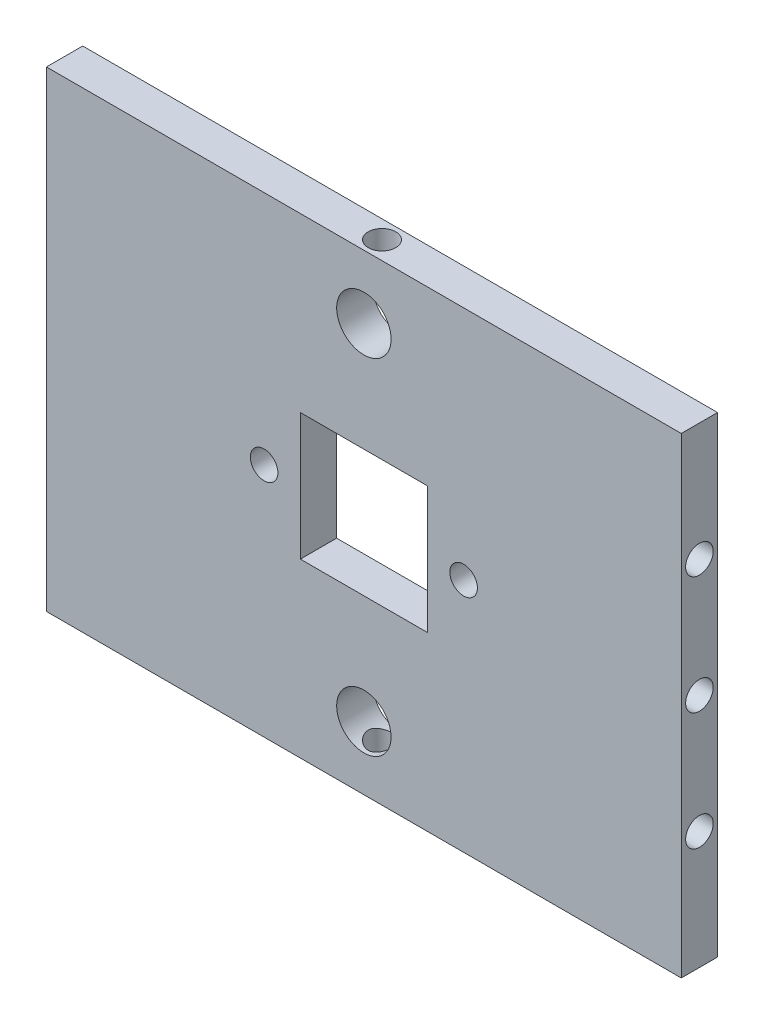
SolidWorks part; units mm, degrees
material "Plain Carbon Steel"
ref_plane "Front Plane" through (0, 0, 0) normal (0, 0, 1) x (1, 0, 0)
ref_plane "Top Plane" through (0, 0, 0) normal (0, 1, 0) x (1, 0, 0)
ref_plane "Right Plane" through (0, 0, 0) normal (1, 0, 0) x (0, 0, -1)
sketch "Sketch1" plane through (0, 0, 0) normal (0, 0, 1) x (1, 0, 0)
  line L1 (55.5625, -41.275) -> (-55.5625, -41.275)
  line L2 (55.5625, -41.275) -> (55.5625, 41.275)
  line L3 (55.5625, 41.275) -> (-55.5625, 41.275)
  line L4 (-55.5625, -41.275) -> (-55.5625, 41.275)
  line L5 (55.5625, -41.275) -> (-55.5625, 41.275) construction
  line L6 (55.5625, 41.275) -> (-55.5625, -41.275) construction
  circle A0 centre (0, 30.1625) radius 4.7625
  circle A1 centre (0, -30.1625) radius 4.7625
  point P0 (0, 0)
  dimension "D3" = 9.525
  dimension "D4" = 9.525
  dimension "D1" = 82.55
  dimension "D2" = 111.125
extrude "Boss-Extrude1" add sketch "Sketch1" along normal blind 6.35
sketch "Sketch2" plane through (55.5625, 0, 0) normal (1, 0, 0) x (0, 0, -1)
  line L0 (-3.175, 41.275) -> (-3.175, 0) construction
  line L1 (-6.35, 41.275) -> (0, 41.275) construction
  line L2 (-3.175, 0) -> (-3.175, -41.275) construction
  line L3 (-6.35, -41.275) -> (0, -41.275) construction
  circle A0 centre (-3.175, 20.6375) radius 2.413
  circle A1 centre (-3.175, 0) radius 2.413
  circle A2 centre (-3.175, -20.6375) radius 2.413
  dimension "D1" = 4.826
  dimension "D2" = 4.826
  dimension "D3" = 4.826
extrude "Cut-Extrude1" cut sketch "Sketch2" against normal blind 12.7
mirror "Mirror1" about plane through (0, 0, 0) normal (1, 0, 0) of "Cut-Extrude1"
sketch "Sketch3" plane through (0, 41.275, 0) normal (0, 1, 0) x (1, 0, 0)
  line L0 (-55.5625, -3.175) -> (55.5625, -3.175) construction
  line L1 (-55.5625, -6.35) -> (-55.5625, 0) construction
  line L2 (55.5625, -6.35) -> (55.5625, 0) construction
  circle A0 centre (0, -3.175) radius 2.413
  dimension "D1" = 4.826
extrude "Cut-Extrude2" cut sketch "Sketch3" against normal blind 12.7
mirror "Mirror2" about plane through (0, 0, 0) normal (0, 1, 0) of "Cut-Extrude2"
sketch "Sketch4" plane through (0, 0, 6.35) normal (0, 0, 1) x (1, 0, 0)
  line L0 (11.1125, 0) -> (17.4625, 0) construction
  line L1 (-11.1125, 0) -> (-17.4625, 0) construction
  line L4 (11.1125, -11.1125) -> (-11.1125, -11.1125)
  line L5 (11.1125, -11.1125) -> (11.1125, 11.1125)
  line L6 (11.1125, 11.1125) -> (-11.1125, 11.1125)
  line L7 (-11.1125, -11.1125) -> (-11.1125, 11.1125)
  line L8 (11.1125, -11.1125) -> (-11.1125, 11.1125) construction
  line L9 (11.1125, 11.1125) -> (-11.1125, -11.1125) construction
  circle A0 centre (17.4625, 0) radius 2.413
  circle A1 centre (-17.4625, 0) radius 2.413
  dimension "D4" = 4.826
  dimension "D6" = 4.826
  dimension "D1" = 22.225
  dimension "D2" = 22.225
  dimension "D3" = 6.35
  dimension "D5" = 6.35
extrude "Cut-Extrude3" cut sketch "Sketch4" against normal blind 7.62
